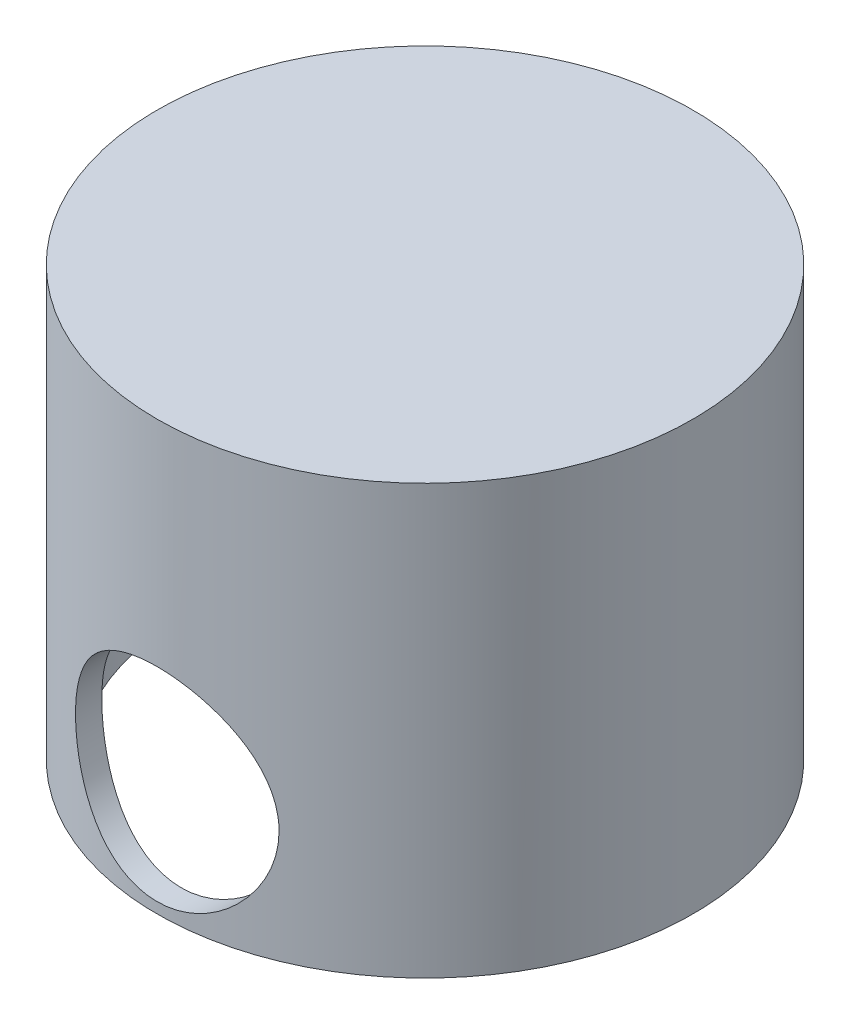
SolidWorks part; units mm, degrees
ref_plane "Front Plane" through (0, 0, 0) normal (0, 0, 1) x (1, 0, 0)
ref_plane "Top Plane" through (0, 0, 0) normal (0, 1, 0) x (1, 0, 0)
ref_plane "Right Plane" through (0, 0, 0) normal (1, 0, 0) x (0, 0, -1)
sketch "Sketch2" plane through (0, 0, 0) normal (0, 1, 0) x (1, 0, 0)
  circle A0 centre (0, 0) radius 5
  dimension "D1" = 10
sketch "Sketch4" plane through (0, 0, 0) normal (0, 1, 0) x (1, 0, 0)
  circle A0 centre (0, 0) radius 4.55
  dimension "D1" = 9.1
extrude "Boss-Extrude1" add sketch "Sketch2" along normal blind 8 contours A0
extrude "Cut-Extrude1" cut sketch "Sketch4" along normal blind 7.1
sketch "Sketch11" plane through (0, 0, 0) normal (0, 0, 1) x (1, 0, 0)
  line L0 (-5, 0) -> (-5, 7.1)
  line L1 (-5, 8) -> (-5, 0) construction
  line L2 (-5, 7.1) -> (-5, 2.1)
  line L3 (-5, 2.1) -> (-1.6, 2.1)
  line L4 (5, 2.1) -> (4.9985, 2.1012)
  line L5 (1.6, 2.1) -> (5, 2.1)
  circle A0 centre (0, 2.1) radius 1.6
  dimension "D4" = 3.2
  dimension "D1" = 7.1
  dimension "D2" = 5
  dimension "D3" = 10
sketch "Sketch12" plane through (0, 0, 0) normal (0, 0, 1) x (1, 0, 0)
  circle A0 centre (0, 2.1) radius 1.9
  dimension "D1" = 3.8
extrude "Cut-Extrude2" cut sketch "Sketch12" against normal through all both and the other way through all
sketch "Sketch13" plane through (0, 0, 0) normal (0, 0, 1) x (1, 0, 0)
  line L0 (1.9, 2.1) -> (1.9, 0)
  line L1 (1.6, 2.1) -> (5, 2.1) construction
  line L2 (-5, 0) -> (5, 0) construction
  line L3 (-1.9, 2.1) -> (-1.9, 0)
  line L4 (-5, 2.1) -> (-1.6, 2.1) construction
  line L5 (-1.9, 0) -> (1.9, 0)
  line L6 (1.9, 2.1) -> (-1.9, 2.1)
  circle A0 centre (0, 2.1) radius 1.9 construction
extrude "Cut-Extrude3" cut sketch "Sketch13" against normal blind 10
